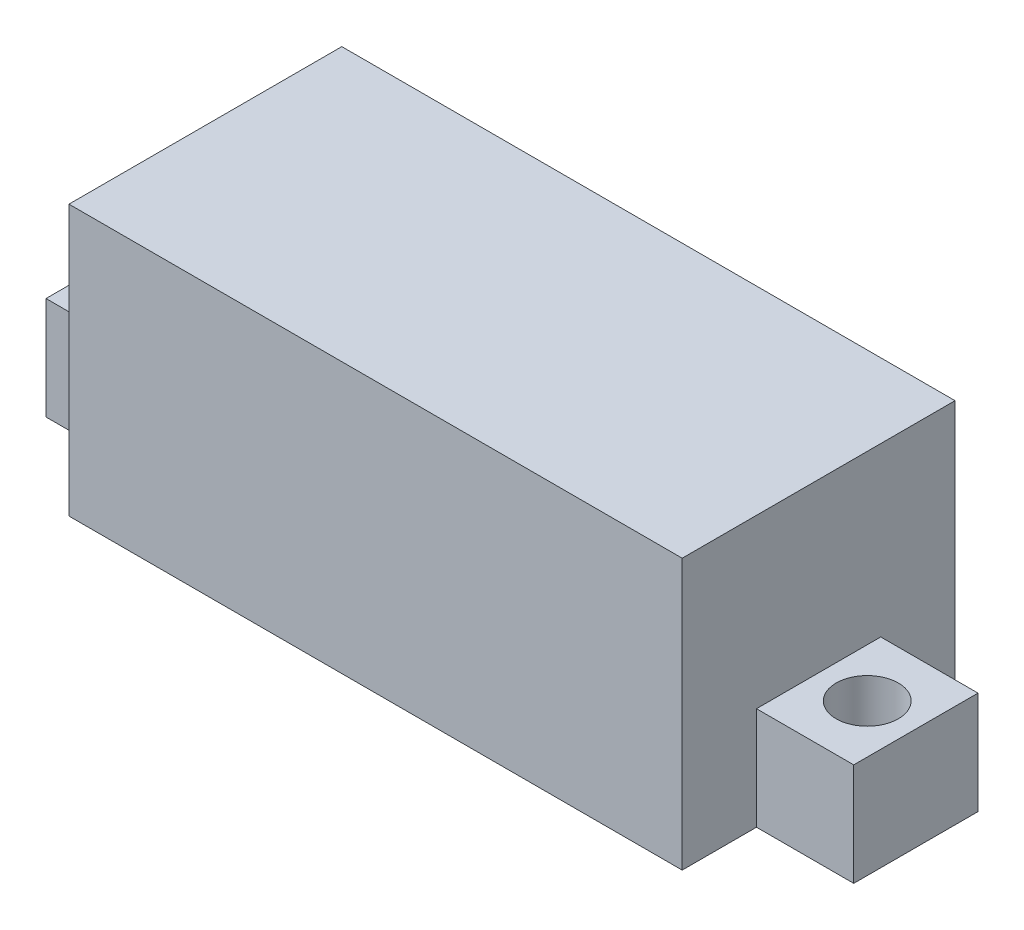
SolidWorks part; units mm, degrees
ref_plane "Front" through (0, 0, 0) normal (0, 0, 1) x (1, 0, 0)
ref_plane "Top" through (0, 0, 0) normal (0, 1, 0) x (1, 0, 0)
ref_plane "Right" through (0, 0, 0) normal (1, 0, 0) x (0, 0, -1)
sketch "ｽｹｯﾁ1" plane through (0, 0, 0) normal (0, 1, 0) x (1, 0, 0)
  line L1 (0, 0) -> (22.7, 0)
  line L2 (0, 0) -> (0, 10.1)
  line L3 (0, 10.1) -> (22.7, 10.1)
  line L4 (22.7, 0) -> (22.7, 10.1)
  dimension "D1" = 22.7
  dimension "D2" = 10.1
extrude "ﾎﾞｽ - 押し出し1" add sketch "ｽｹｯﾁ1" along normal blind 10
sketch "ｽｹｯﾁ2" plane through (0, 0, 0) normal (0, -1, 0) x (1, 0, 0)
  line L0 (0, -5.05) -> (22.7, -5.05) construction
  line L1 (0, -10.1) -> (0, 0) construction
  line L2 (22.7, 0) -> (22.7, -10.1) construction
  line L3 (-3.6, -5.05) -> (0, -5.05) construction
  line L4 (0, -2.75) -> (-3.6, -2.75)
  line L5 (0, -2.75) -> (0, -7.35)
  line L6 (0, -7.35) -> (-3.6, -7.35)
  line L7 (-3.6, -2.75) -> (-3.6, -7.35)
  line L8 (11.35, 0) -> (11.35, -10.1) construction
  line L9 (0, 0) -> (22.7, 0) construction
  line L10 (22.7, -10.1) -> (0, -10.1) construction
  line L11 (26.3, -5.05) -> (22.7, -5.05) construction
  line L12 (26.3, -2.75) -> (26.3, -7.35)
  line L13 (22.7, -7.35) -> (26.3, -7.35)
  line L14 (22.7, -2.75) -> (22.7, -7.35)
  line L15 (22.7, -2.75) -> (26.3, -2.75)
  circle A0 centre (-1.8, -5.05) radius 1.15
  circle A1 centre (24.5, -5.05) radius 1.15
  dimension "D3" = 2.3
  dimension "D1" = 3.6
  dimension "D2" = 4.6
extrude "ﾎﾞｽ - 押し出し2" add sketch "ｽｹｯﾁ2" against normal blind 3.8
ref_plane "平面1" through (11.35, 0, 0) normal (1, 0, 0) x (0, 0, -1)
ref_plane "平面2" through (0, 0, -5.05) normal (0, 0, -1) x (-1, 0, 0)
